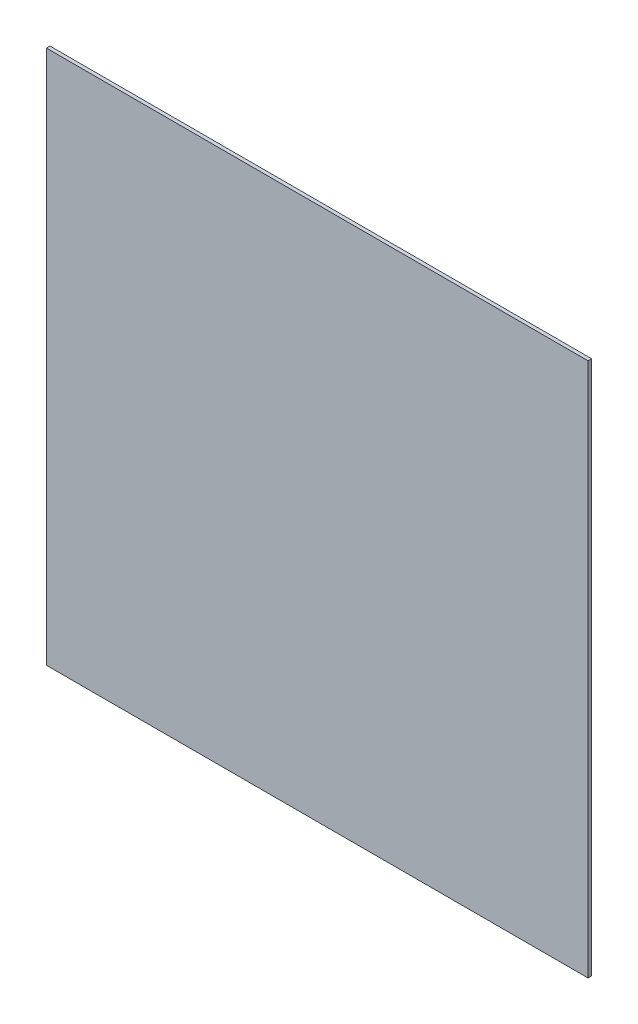
SolidWorks part; units mm, degrees
ref_plane "Спереди" through (0, 0, 0) normal (0, 0, 1) x (1, 0, 0)
ref_plane "Сверху" through (0, 0, 0) normal (0, 1, 0) x (1, 0, 0)
ref_plane "Справа" through (0, 0, 0) normal (1, 0, 0) x (0, 0, -1)
sketch "Эскиз1" plane through (0, 0, 0) normal (0, 0, 1) x (1, 0, 0)
  line L1 (0, 0) -> (1520, 0)
  line L2 (0, 0) -> (0, 1500)
  line L3 (0, 1500) -> (1520, 1500)
  line L4 (1520, 0) -> (1520, 1500)
  dimension "D1" = 1520
  dimension "D2" = 1500
extrude "Бобышка-Вытянуть1" add sketch "Эскиз1" along normal blind 10
